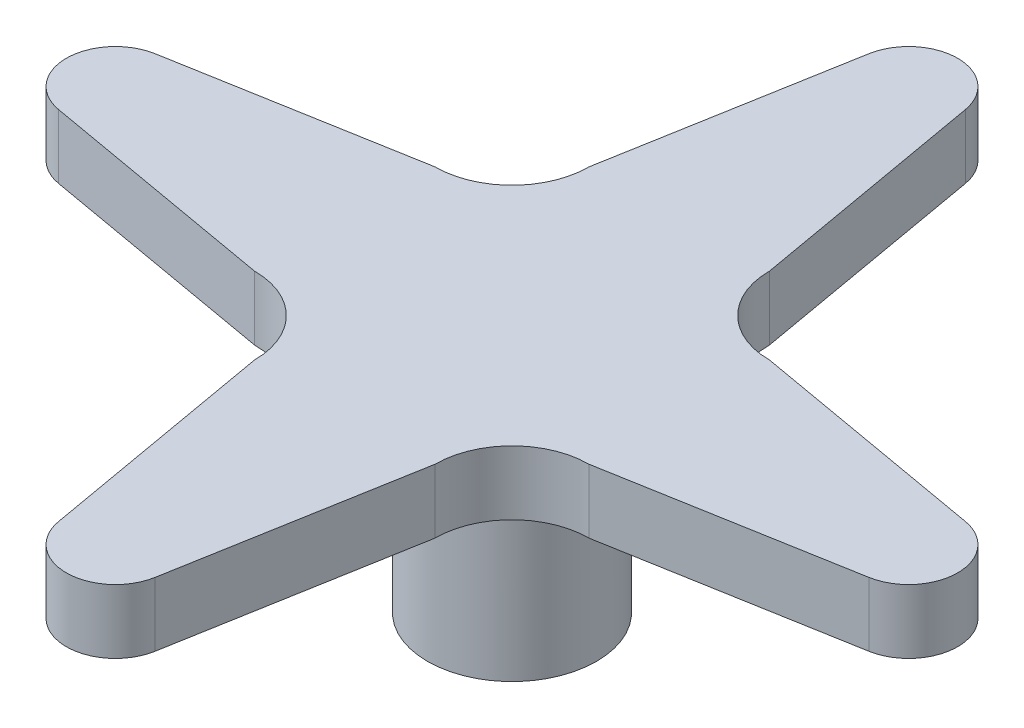
SolidWorks part; units mm, degrees
ref_plane "Front Plane" through (0, 0, 0) normal (0, 0, 1) x (1, 0, 0)
ref_plane "Top Plane" through (0, 0, 0) normal (0, 1, 0) x (1, 0, 0)
ref_plane "Right Plane" through (0, 0, 0) normal (1, 0, 0) x (0, 0, -1)
sketch "Sketch2" plane through (0, 0, 0) normal (0, 1, 0) x (1, 0, 0)
  line L0 (0, 0) -> (0, 50000) construction
  line L1 (2, 16.7718) -> (3.7365, 6.9237)
  line L2 (0, 0) -> (15.933, 15.933) construction
  line L3 (0, -55) -> (0, 55) construction
  line L4 (-12.8998, 18.45) -> (12.8998, 18.45) construction
  line L5 (-55, 0) -> (55, 0) construction
  line L6 (1.1393, 8.2007) -> (8.2007, 1.1393) construction
  line L7 (-2, 16.7718) -> (-3.7365, 6.9237)
  line L8 (16.7718, -2) -> (6.9237, -3.7365)
  line L9 (16.7718, 2) -> (6.9237, 3.7365)
  line L10 (-2, -16.7718) -> (-3.7365, -6.9237)
  line L11 (2, -16.7718) -> (3.7365, -6.9237)
  line L12 (-16.7718, 2) -> (-6.9237, 3.7365)
  line L13 (-16.7718, -2) -> (-6.9237, -3.7365)
  arc A1 (2, 16.7718) -> (-2, 16.7718) centre (0, 16.4191) ccw
  arc A2 (3.7365, 6.9237) -> (4.67, 4.67) centre (6.9237, 6.9237) ccw
  arc A3 (-3.7365, 6.9237) -> (-4.67, 4.67) centre (-6.9237, 6.9237) cw
  arc A4 (16.7718, -2) -> (16.7718, 2) centre (16.4191, 0) ccw
  arc A5 (6.9237, 3.7365) -> (4.67, 4.67) centre (6.9237, 6.9237) cw
  arc A6 (6.9237, -3.7365) -> (4.67, -4.67) centre (6.9237, -6.9237) ccw
  arc A7 (-2, -16.7718) -> (2, -16.7718) centre (0, -16.4191) ccw
  arc A8 (3.7365, -6.9237) -> (4.67, -4.67) centre (6.9237, -6.9237) cw
  arc A9 (-3.7365, -6.9237) -> (-4.67, -4.67) centre (-6.9237, -6.9237) ccw
  arc A10 (-16.7718, 2) -> (-16.7718, -2) centre (-16.4191, 0) ccw
  arc A11 (-6.9237, -3.7365) -> (-4.67, -4.67) centre (-6.9237, -6.9237) cw
  arc A12 (-6.9237, 3.7365) -> (-4.67, 4.67) centre (-6.9237, 6.9237) ccw
  point P12 (0, 18.45)
  point P24 (4.67, 4.67)
  point P55 (0, 0)
  dimension "D4" = 18.45
  dimension "D6" = 4
  dimension "D2" = 10
  dimension "D3" = 10
  dimension "D5" = 2
  dimension "D7" = 45
  dimension "D8" = 90
extrude "Boss-Extrude1" add sketch "Sketch2" along normal mid plane 2.65
ref_plane "Plane1" through (0, 0.325, 0) normal (0, 1, 0) x (1, 0, 0)
sketch "Sketch5" plane through (0, -1.325, 0) normal (0, -1, 0) x (1, 0, 0)
  circle A0 centre (0, 0) radius 3.5
  dimension "D1" = 7
extrude "Boss-Extrude4" add sketch "Sketch5" along normal blind 8
sketch "Sketch6" plane through (0, -9.325, 0) normal (0, -1, 0) x (1, 0, 0)
  line L0 (-1.4595, -1.475) -> (1.4595, -1.475)
  circle A0 centre (0, 0) radius 2.075
  point P5 (0, 2.075)
  dimension "D2" = 4.15
  dimension "D1" = 3.55
extrude "Cut-Extrude1" cut sketch "Sketch6" against normal up to surface (8 mm away) contours L0 A0
